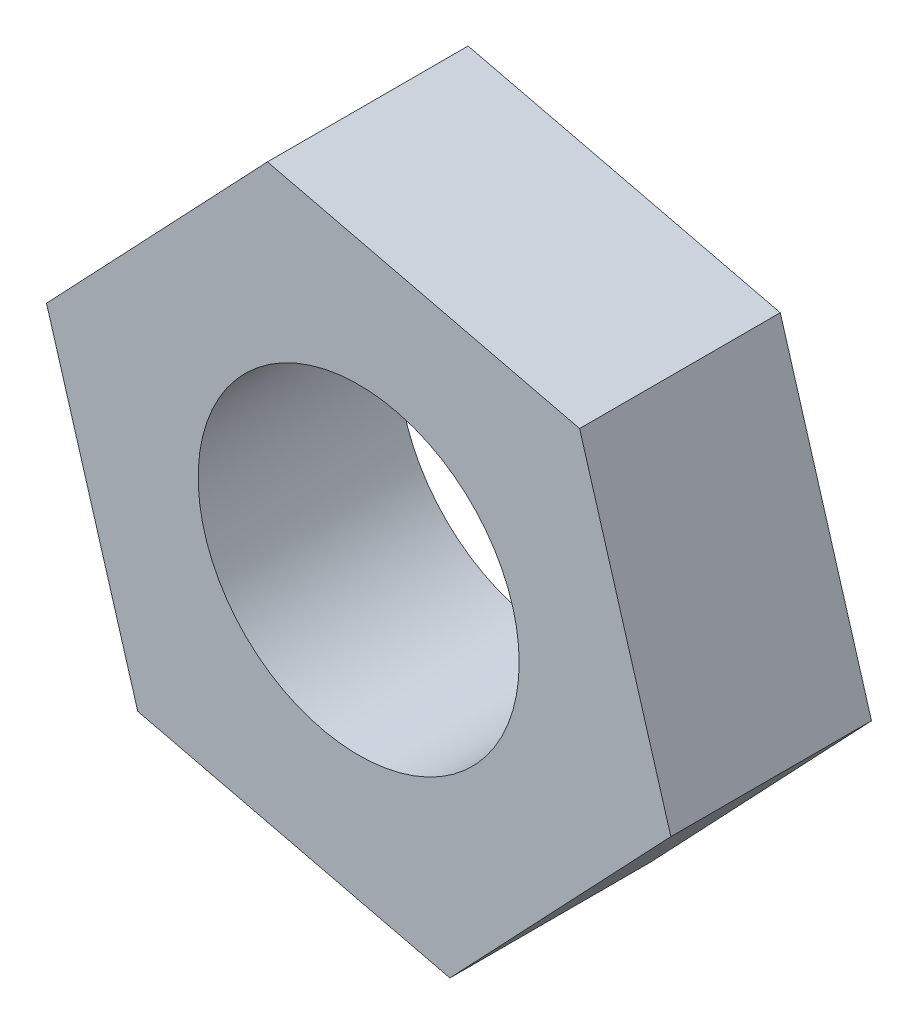
SolidWorks part; units mm, degrees
ref_plane "前视基准面" through (0, 0, 0) normal (0, 0, 1) x (1, 0, 0)
ref_plane "上视基准面" through (0, 0, 0) normal (0, 1, 0) x (1, 0, 0)
ref_plane "右视基准面" through (0, 0, 0) normal (1, 0, 0) x (0, 0, -1)
sketch "草图1" plane through (0, 0, 0) normal (0, 0, 1) x (1, 0, 0)
  line L1 (5.5057, 5.804) -> (-2.2736, 7.6701)
  line L2 (-2.2736, 7.6701) -> (-7.7793, 1.8661)
  line L3 (-7.7793, 1.8661) -> (-5.5057, -5.804)
  line L4 (-5.5057, -5.804) -> (2.2736, -7.6701)
  line L5 (2.2736, -7.6701) -> (7.7793, -1.8661)
  line L6 (7.7793, -1.8661) -> (5.5057, 5.804)
  circle A0 centre (0, 0) radius 8 construction
  dimension "D1" = 16
extrude "凸台-拉伸1" add sketch "草图1" along normal blind 5
sketch "草图2" plane through (0, 0, 5) normal (0, 0, 1) x (1, 0, 0)
  circle A0 centre (0, 0) radius 4
  dimension "D1" = 8
extrude "切除-拉伸1" cut sketch "草图2" against normal through all
